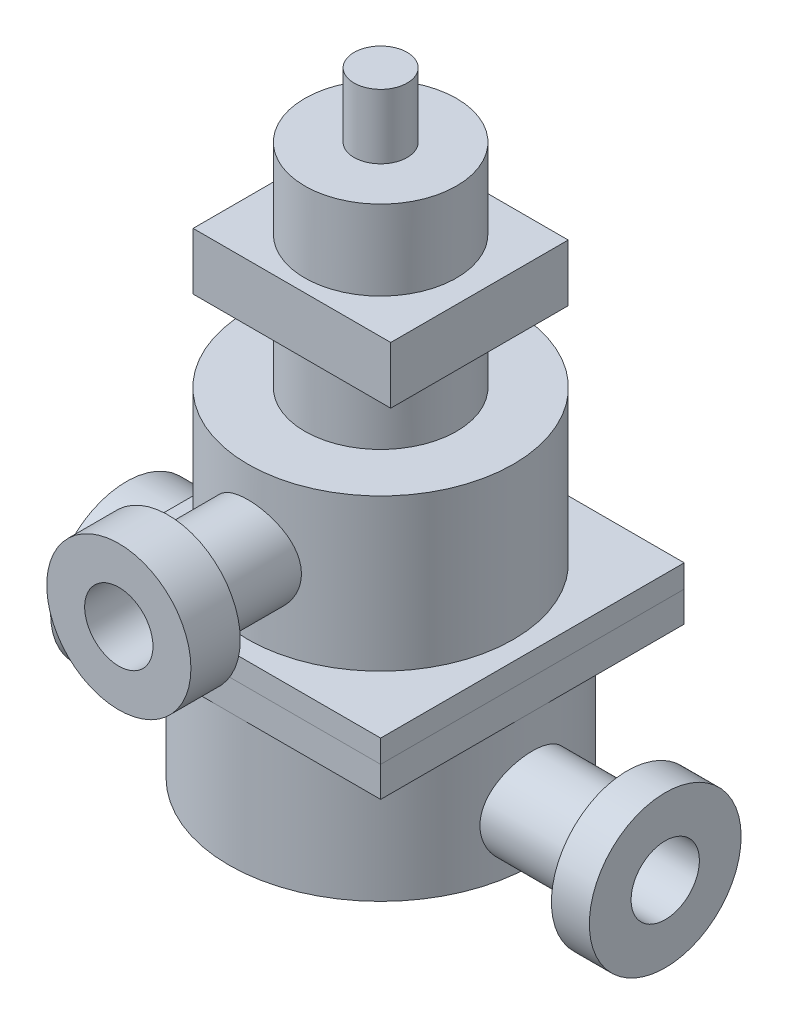
SolidWorks part; units mm, degrees
ref_plane "Front Plane" through (0, 0, 0) normal (0, 0, 1) x (1, 0, 0)
ref_plane "Top Plane" through (0, 0, 0) normal (0, 1, 0) x (1, 0, 0)
ref_plane "Right Plane" through (0, 0, 0) normal (1, 0, 0) x (0, 0, -1)
sketch "Sketch1" plane through (0, 0, 0) normal (0, 1, 0) x (1, 0, 0)
  circle A0 centre (0, 0) radius 40
extrude "Boss-Extrude1" add sketch "Sketch1" along normal blind 35
sketch "Sketch2" plane through (0, 0, 0) normal (1, 0, 0) x (0, 0, -1)
  line L0 (0, 0) -> (0, 28.1243) construction
  line L1 (0, 27.5) -> (0, -27.5) construction
  circle A0 centre (0, 14.0621) radius 12
  point P7 (0, 14.0621)
extrude "Boss-Extrude2" add sketch "Sketch2" along normal blind 65 and the other way blind 54
sketch "Sketch3" plane through (65, 0, 0) normal (1, 0, 0) x (0, 0, -1)
  line L0 (0, 2.0621) -> (0, 26.0621) construction
  circle A0 centre (0, 14.0621) radius 12 construction
  circle A1 centre (0, 14.0621) radius 12 construction
  circle A2 centre (0, 14.0621) radius 20
extrude "Boss-Extrude3" add sketch "Sketch3" along normal blind 10
sketch "Sketch6" plane through (0, 35, 0) normal (0, 1, 0) x (1, 0, 0)
  line L0 (0, 40) -> (-40, 40)
  line L1 (-40, 40) -> (-40, -40)
  line L2 (-40, -40) -> (40, -40)
  line L3 (40, -40) -> (40, 40)
  line L4 (40, 40) -> (0, 40)
  circle A0 centre (0, 0) radius 40 construction
extrude "Boss-Extrude4" add sketch "Sketch6" along normal blind 8
sketch "Sketch8" plane through (0, 43, 0) normal (0, 1, 0) x (1, 0, 0)
  line L0 (-40, 40) -> (40, 40)
  line L1 (40, 40) -> (40, -40)
  line L2 (40, -40) -> (-40, -40)
  line L3 (-40, -40) -> (-40, 40)
extrude "Boss-Extrude5" add sketch "Sketch8" along normal blind 6 separate body
sketch "Sketch9" plane through (0, 49, 0) normal (0, 1, 0) x (1, 0, 0)
  circle A0 centre (0, 0) radius 35
extrude "Boss-Extrude6" add sketch "Sketch9" along normal blind 40
sketch "Sketch10" plane through (0, 89, 0) normal (0, 1, 0) x (1, 0, 0)
  circle A0 centre (0, 0) radius 20
extrude "Boss-Extrude7" add sketch "Sketch10" along normal blind 56
ref_plane "Plane1" through (0, 109, 0) normal (0, 1, 0) x (1, 0, 0)
sketch "Sketch13" plane through (0, 109, 0) normal (0, 1, 0) x (1, 0, 0)
  line L1 (-26.042, -23.3841) -> (26.042, -23.3841)
  line L2 (-26.042, -23.3841) -> (-26.042, 23.3841)
  line L3 (-26.042, 23.3841) -> (26.042, 23.3841)
  line L4 (26.042, -23.3841) -> (26.042, 23.3841)
  line L5 (-26.042, -23.3841) -> (26.042, 23.3841) construction
  line L6 (-26.042, 23.3841) -> (26.042, -23.3841) construction
  circle A0 centre (0, 0) radius 35 construction
  point P0 (0, 0)
  point P8 (-93.2015, -33.4002)
  dimension "D1" = 52.084
extrude "Boss-Extrude8" add sketch "Sketch13" along normal blind 15
sketch "Sketch14" plane through (0, 0, 0) normal (0, 0, 1) x (1, 0, 0)
  line L0 (0, 48.9153) -> (0, 88.9178) construction
  line L1 (0, -44) -> (0, 44) construction
  circle A0 centre (0, 68.9166) radius 12
extrude "Boss-Extrude9" add sketch "Sketch14" along normal blind 56
sketch "Sketch15" plane through (0, 0, 56) normal (0, 0, 1) x (1, 0, 0)
  line L0 (0, 56.9166) -> (0, 80.9166) construction
  line L1 (0, -44) -> (0, 44) construction
  circle A0 centre (0, 68.9166) radius 12 construction
  circle A1 centre (0, 68.9166) radius 19
extrude "Boss-Extrude10" add sketch "Sketch15" along normal blind 13
sketch "Sketch21" plane through (0, 145, 0) normal (0, 1, 0) x (1, 0, 0)
  circle A0 centre (0, 0) radius 7
extrude "Boss-Extrude12" add sketch "Sketch21" along normal blind 17
sketch "Sketch18" plane through (-54, 0, 0) normal (-1, 0, 0) x (0, 0, 1)
  line L0 (0, 2.0621) -> (0, 26.0621) construction
  circle A0 centre (0, 14.0621) radius 12 construction
  circle A1 centre (0, 14.0621) radius 12 construction
  circle A2 centre (0, 14.0621) radius 20
extrude "Boss-Extrude11" add sketch "Sketch18" along normal blind 13
sketch "Sketch16" plane through (0, 0, 69) normal (0, 0, 1) x (1, 0, 0)
  line L0 (0, 49.9166) -> (0, 87.9166) construction
  line L1 (0, 77.9166) -> (0, 87.9166) construction
  circle A0 centre (0, 68.9166) radius 19 construction
  circle A1 centre (0, 68.9166) radius 9
  circle A2 centre (0, 82.9166) radius 2
  circle A3 centre (8.229, 80.2428) radius 2
  circle A4 centre (13.3148, 73.2428) radius 2
  circle A5 centre (13.3148, 64.5903) radius 2
  circle A6 centre (8.229, 57.5903) radius 2
  circle A7 centre (0, 54.9166) radius 2
  circle A8 centre (-8.229, 57.5903) radius 2
  circle A9 centre (-13.3148, 64.5903) radius 2
  circle A10 centre (-13.3148, 73.2428) radius 2
  circle A11 centre (-8.229, 80.2428) radius 2
  point P30 (0, 68.9166)
  dimension "D1" = 10
sketch "Sketch19" plane through (-67, 0, 0) normal (-1, 0, 0) x (0, 0, 1)
  line L0 (0, -5.9379) -> (0, 34.0621) construction
  circle A0 centre (0, 14.0621) radius 20 construction
sketch "Sketch20" plane through (-67, 0, 0) normal (-1, 0, 0) x (0, 0, 1)
  line L0 (0, -5.9379) -> (0, 34.0621) construction
  circle A0 centre (0, 14.0621) radius 9
extrude "Cut-Extrude3" cut sketch "Sketch20" against normal blind 37
sketch "Sketch4" plane through (75, 0, 0) normal (1, 0, 0) x (0, 0, -1)
  circle A1 centre (0, 14.0621) radius 9
  point P10 (0, 14.0621)
  point P30 (0, 14.0621)
extrude "Cut-Extrude2" cut sketch "Sketch4" against normal blind 159
extrude "Cut-Extrude4" cut sketch "Sketch16" against normal blind 70 contours A1
